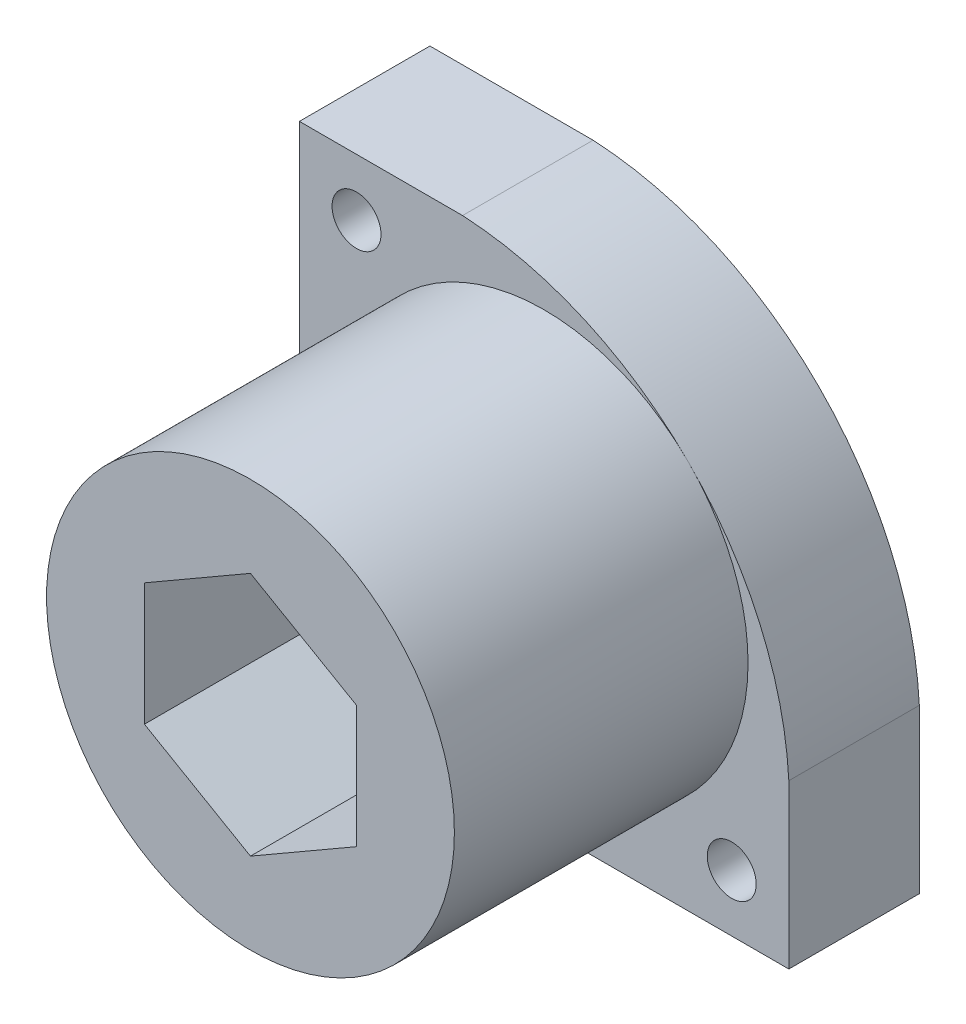
SolidWorks part; units mm, degrees
ref_plane "Ön Düzlem" through (0, 0, 0) normal (0, 0, 1) x (1, 0, 0)
ref_plane "Üst Düzlem" through (0, 0, 0) normal (0, 1, 0) x (1, 0, 0)
ref_plane "Sağ Düzlem" through (0, 0, 0) normal (1, 0, 0) x (0, 0, -1)
sketch "Çizim1" plane through (0, 0, 0) normal (0, 0, 1) x (1, 0, 0)
  line L1 (0, 0) -> (30, 0)
  line L2 (0, 0) -> (0, 30)
  line L3 (0, 30) -> (30, 30)
  line L4 (30, 0) -> (30, 30)
  dimension "D1" = 30
extrude "Yükseklik-Ekstrüzyon1" add sketch "Çizim1" along normal blind 8
sketch "Çizim2" plane through (0, 0, 8) normal (0, 0, 1) x (1, 0, 0)
  line L0 (30, 0) -> (30, 30) construction
  line L1 (0, 0) -> (30, 0) construction
  line L3 (15, 22.5056) -> (8.5, 18.7528)
  line L4 (8.5, 18.7528) -> (8.5, 11.2472)
  line L5 (8.5, 11.2472) -> (15, 7.4944)
  line L6 (15, 7.4944) -> (21.5, 11.2472)
  line L7 (21.5, 11.2472) -> (21.5, 18.7528)
  line L8 (21.5, 18.7528) -> (15, 22.5056)
  circle A0 centre (15, 15) radius 12.5
  circle A1 centre (15, 15) radius 6.5 construction
  dimension "D1" = 25
  dimension "D2" = 15
  dimension "D3" = 15
  dimension "D4" = 13
extrude "Yükseklik-Ekstrüzyon2" add sketch "Çizim2" along normal blind 8
sketch "Çizim3" plane through (0, 0, 8) normal (0, 0, 1) x (1, 0, 0)
  circle A0 centre (15, 15) radius 5.5
  circle A1 centre (15, 15) radius 12.5 construction
  dimension "D1" = 11
extrude "Kes-Ekstrüzyon1" cut sketch "Çizim3" against normal blind 8
sketch "Çizim4" plane through (0, 0, 8) normal (0, 0, 1) x (1, 0, 0)
  line L0 (30, 30) -> (0, 30) construction
  line L1 (0, 30) -> (0, 0) construction
  line L2 (30, 0) -> (30, 30) construction
  line L3 (0, 0) -> (30, 0) construction
  circle A0 centre (3.5, 26.5) radius 1.5
  circle A1 centre (26.5, 26.5) radius 1.5
  circle A2 centre (26.5, 3.5) radius 1.5
  circle A3 centre (3.5, 3.5) radius 1.5
  dimension "D1" = 3
  dimension "D2" = 3.5
  dimension "D3" = 3.5
  dimension "D4" = 3.5
  dimension "D5" = 3.5
  dimension "D6" = 3.5
  dimension "D7" = 3.5
  dimension "D8" = 3.5
  dimension "D9" = 3.5
extrude "Kes-Ekstrüzyon2" cut sketch "Çizim4" against normal blind 8
sketch "Çizim5" plane through (0, 0, 16) normal (0, 0, 1) x (1, 0, 0)
  line L0 (15, 22.5056) -> (8.5, 18.7528) construction
  line L1 (15, 22.5056) -> (8.5, 18.7528)
  line L2 (8.5, 18.7528) -> (8.5, 11.2472)
  line L3 (8.5, 11.2472) -> (15, 7.4944)
  line L4 (15, 7.4944) -> (21.5, 11.2472)
  line L5 (21.5, 11.2472) -> (21.5, 18.7528)
  line L6 (21.5, 18.7528) -> (15, 22.5056)
  line L7 (15, 22.5056) -> (8.5, 18.7528) construction
  circle A0 centre (15, 15) radius 12.5
  circle A1 centre (15, 15) radius 12.5 construction
  circle A2 centre (15, 15) radius 6.5 construction
extrude "Yükseklik-Ekstrüzyon3" add sketch "Çizim5" along normal blind 10
sketch "Çizim6" plane through (0, 0, 8) normal (0, 0, 1) x (1, 0, 0)
  line L0 (30, 30) -> (0, 30) construction
  line L1 (30, 0) -> (30, 30) construction
  line L2 (10, 30) -> (30, 30)
  line L3 (30, 30) -> (30, 10)
  arc A0 (10, 30) -> (30, 10) centre (8.8946, 8.8946) cw
  circle A1 centre (15, 15) radius 12.5 construction
  dimension "D1" = 10
  dimension "D2" = 10
extrude "Kes-Ekstrüzyon3" cut sketch "Çizim6" against normal blind 10
